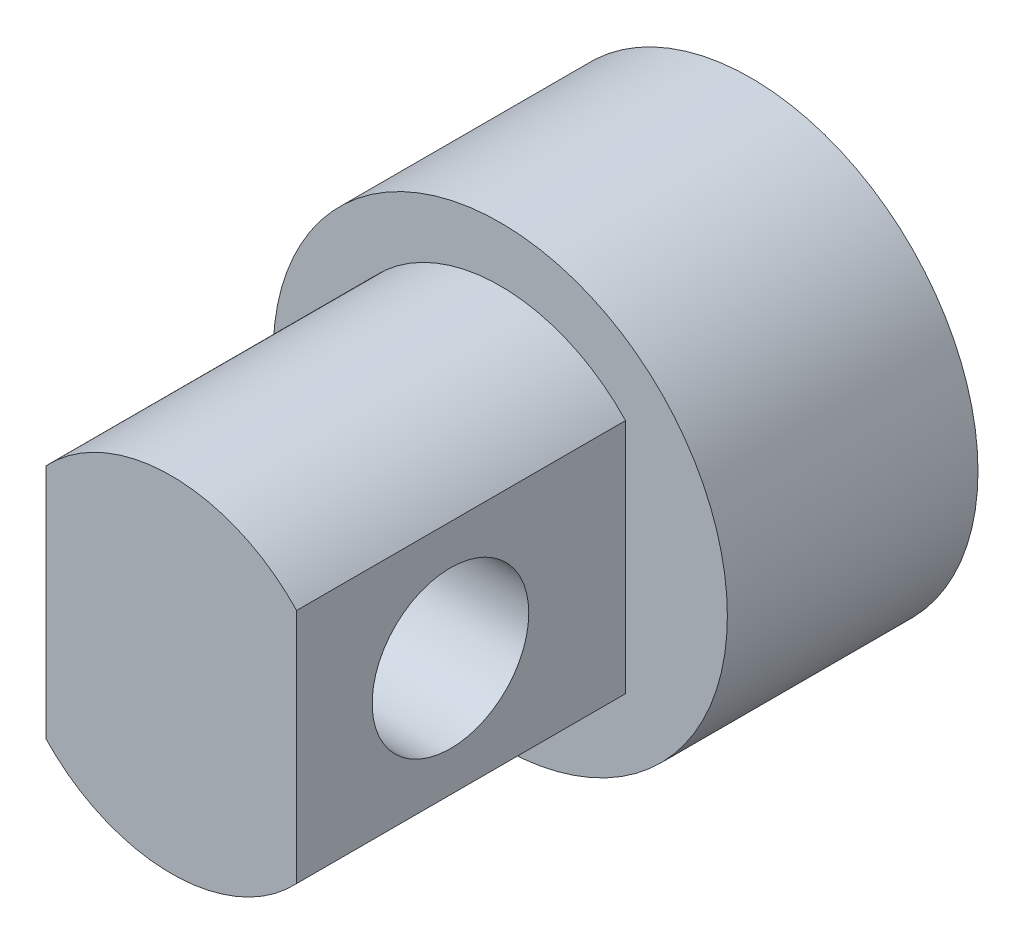
SolidWorks part; units mm, degrees
ref_plane "Front Plane" through (0, 0, 0) normal (0, 0, 1) x (1, 0, 0)
ref_plane "Top Plane" through (0, 0, 0) normal (0, 1, 0) x (1, 0, 0)
ref_plane "Right Plane" through (0, 0, 0) normal (1, 0, 0) x (0, 0, -1)
sketch "Sketch1" plane through (0, 0, 0) normal (0, 0, 1) x (1, 0, 0)
  line L2 (-8, 7.5498) -> (-8, -7.5498)
  line L4 (8, 7.5498) -> (8, -7.5498)
  arc A0 (-8, -7.5498) -> (8, -7.5498) centre (0, 0) ccw
  arc A1 (8, 7.5498) -> (-8, 7.5498) centre (0, 0) ccw
extrude "Boss-Extrude1" add sketch "Sketch1" along normal blind 21
sketch "Sketch3" plane through (0, 0, 0) normal (0, 0, 1) x (1, 0, 0)
  circle A0 centre (0, 0) radius 14.5
extrude "Boss-Extrude2" add sketch "Sketch3" against normal blind 16
sketch "Sketch4" plane through (0, 0, 0) normal (1, 0, 0) x (0, 0, -1)
  line L0 (-36.2283, 0) -> (13.1602, 0) construction
  line L1 (-21.1791, -13.6142) -> (-21.1791, 16.2104) construction
  circle A0 centre (-11.1791, 0) radius 5
  dimension "D1" = 10
extrude "Cut-Extrude1" cut sketch "Sketch4" against normal through all both and the other way through all
